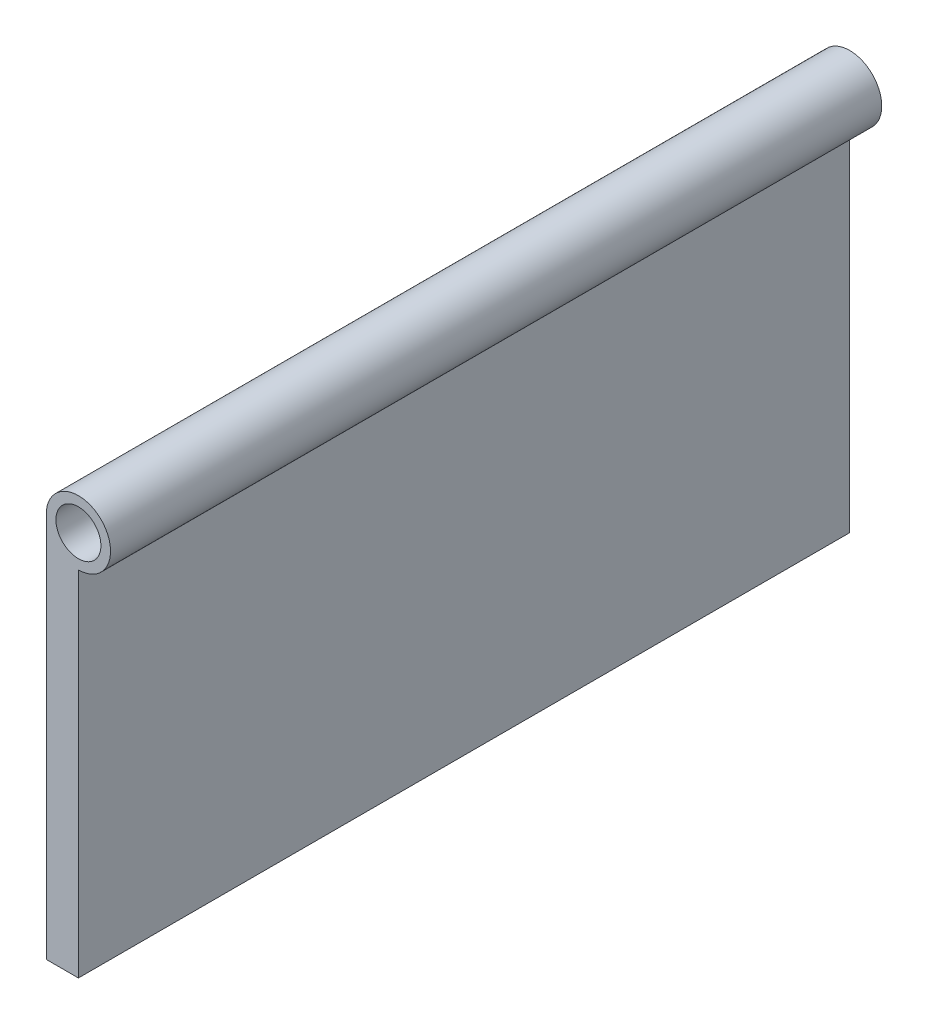
SolidWorks part; units mm, degrees
ref_plane "Front" through (0, 0, 0) normal (0, 0, 1) x (1, 0, 0)
ref_plane "Top" through (0, 0, 0) normal (0, 1, 0) x (1, 0, 0)
ref_plane "Right" through (0, 0, 0) normal (1, 0, 0) x (0, 0, -1)
sketch "Эскиз1" plane through (0, 0, 0) normal (0, 0, 1) x (1, 0, 0)
  line L0 (0, 0) -> (0, 60)
extrude "Вытянуть-Тонкостенный1" add sketch "Эскиз1" along normal mid plane 120 thin
sketch "Эскиз2" plane through (0, 0, 60) normal (0, 0, 1) x (1, 0, 0)
  circle A0 centre (5, 60) radius 5
sweep "По траектории1" add profiles "Эскиз2" path edge at (5, 60, 0)
sketch "Эскиз3" plane through (0, 0, 60) normal (0, 0, 1) x (1, 0, 0)
  circle A0 centre (5, 60) radius 3.5
  arc A1 (5, 55) -> (0, 60) centre (5, 60) ccw construction
extrude "Вырез-Вытянуть4" cut sketch "Эскиз3" against normal through all
